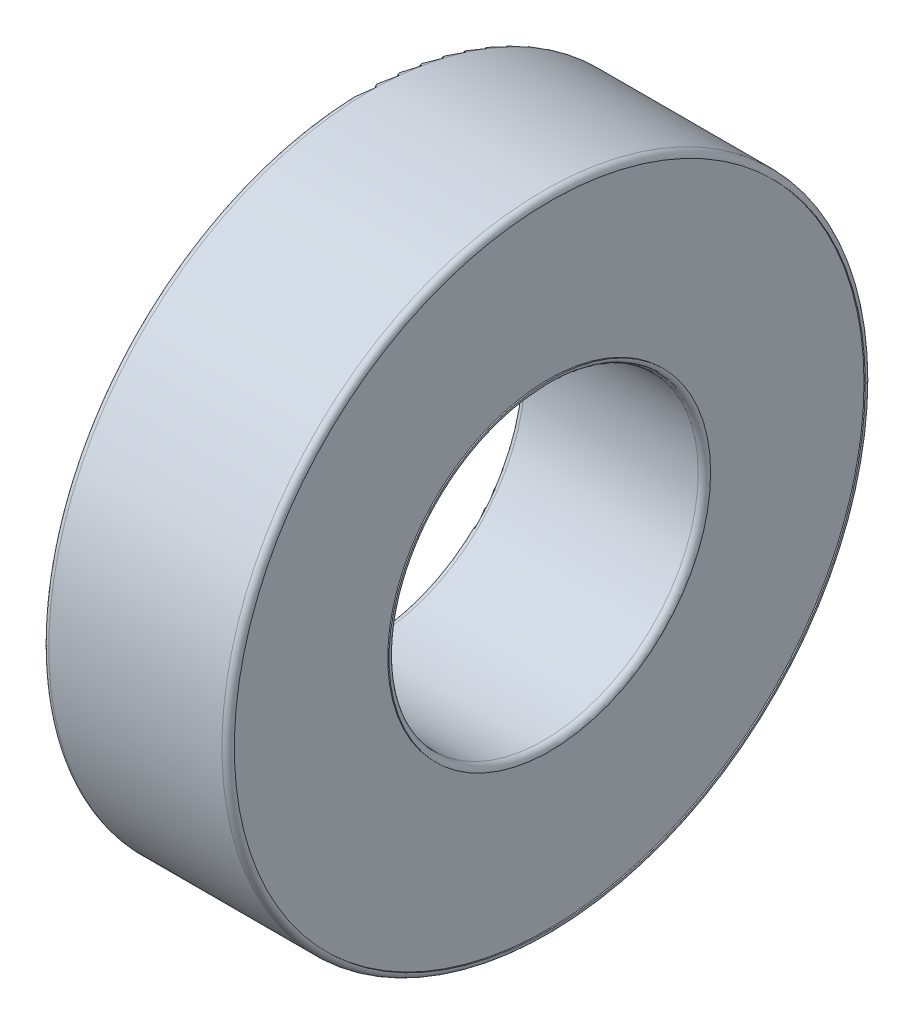
SolidWorks part; units mm, degrees
material "PW60:22:C1:0:1:2:Sc:3:Re:27:"
ref_plane "Plane1  ZX" through (0, 0, 0) normal (0, 0, 1) x (1, 0, 0)
ref_plane "Plane2  XY" through (0, 0, 0) normal (0, 1, 0) x (1, 0, 0)
ref_plane "Plane3  ZY" through (0, 0, 0) normal (1, 0, 0) x (0, 0, -1)
sketch "Sketch1" plane through (0, 0, 0) normal (1, 0, 0) x (0, 0, -1)
  circle A0 centre (0, 0) radius 12.5
  circle A1 centre (0, 0) radius 26
  dimension "D1" = 25
  dimension "D2" = 52
extrude "Base-Extrude" add sketch "Sketch1" along normal blind 15
fillet "Raccordo1" radius 0.5 4 edges at (0, 0, -26) (15, 0, -26) (0, 0, -12.5) (15, 0, -12.5)
sketch "Schizzo1" plane through (0, 0, 0) normal (-1, 0, 0) x (0, 0, 1)
  circle A0 centre (0, 0) radius 13 construction
  circle A1 centre (0, 0) radius 25.5
  circle A2 centre (0, 0) radius 25.5
  circle A3 centre (0, 0) radius 13
  dimension "D1" = 0
extrude "Taglio-Estrusione1" cut sketch "Schizzo1" against normal blind 0.1
sketch "Schizzo2" plane through (15, 0, 0) normal (1, 0, 0) x (0, 0, -1)
  circle A0 centre (0, 0) radius 13 construction
  circle A1 centre (0, 0) radius 25.5
  circle A2 centre (0, 0) radius 25.5
  circle A3 centre (0, 0) radius 13
  dimension "D1" = 0
extrude "Taglio-Estrusione2" cut sketch "Schizzo2" against normal blind 0.1
